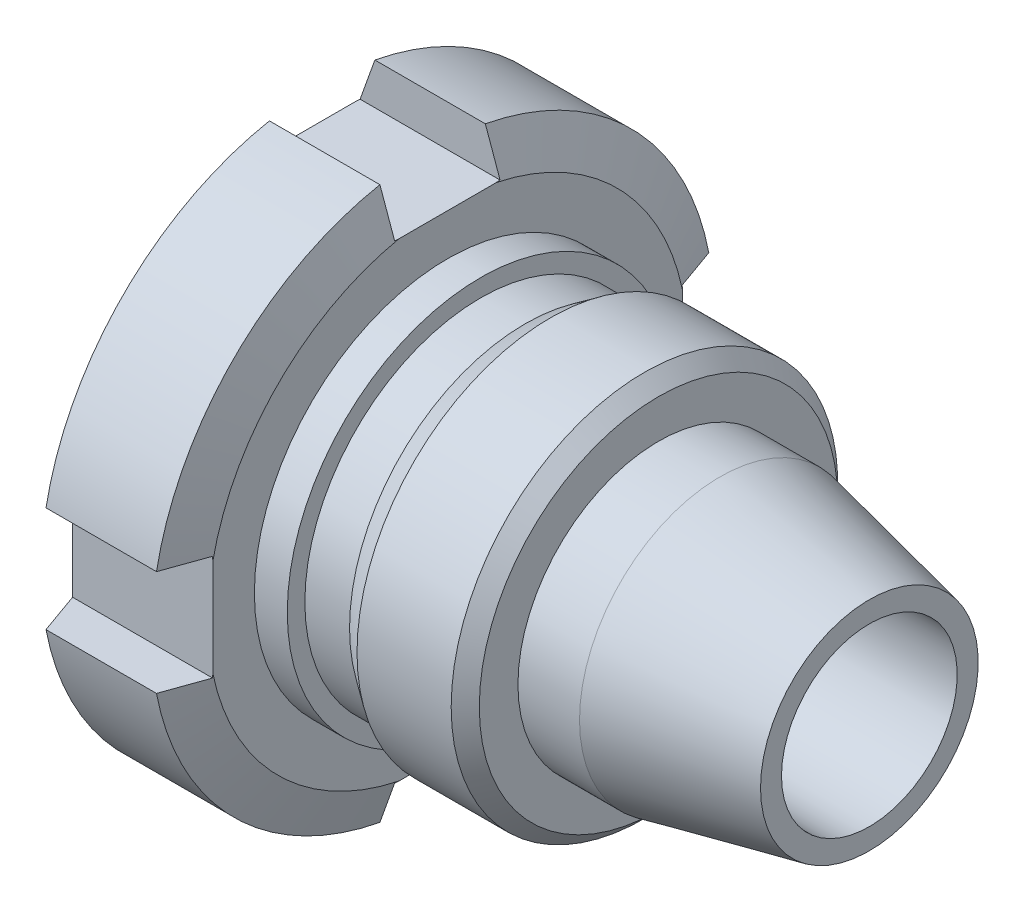
SolidWorks part; units mm, degrees
material "6061-T6 (SS)"
ref_plane "Front Plane" through (0, 0, 0) normal (0, 0, 1) x (1, 0, 0)
ref_plane "Top Plane" through (0, 0, 0) normal (0, 1, 0) x (1, 0, 0)
ref_plane "Right Plane" through (0, 0, 0) normal (1, 0, 0) x (0, 0, -1)
sketch "Sketch1" plane through (0, 0, 0) normal (0, 0, 1) x (1, 0, 0)
  line L0 (0, 6.35) -> (0, 21.6662)
  line L1 (1.359, 25.4) -> (11.341, 25.4)
  line L2 (12.7, 21.6662) -> (12.7, 17.4625)
  line L3 (12.7, 17.4625) -> (15.6718, 17.4625)
  line L4 (15.6718, 17.4625) -> (15.6718, 15.875)
  line L5 (15.6718, 15.875) -> (19.7104, 15.875)
  line L6 (19.7104, 15.875) -> (21.971, 17.4625)
  line L7 (21.971, 17.4625) -> (30.48, 17.4625)
  line L8 (31.75, 16.1925) -> (31.75, 12.7)
  line L9 (31.75, 12.7) -> (37.3126, 12.7)
  line L10 (37.3126, 12.7) -> (50.8, 9.8332)
  line L11 (50.8, 9.8332) -> (50.8, 7.9375)
  line L12 (50.8, 7.9375) -> (38.1, 7.9375)
  line L14 (37.1461, 6.35) -> (0, 6.35)
  line L15 (0, 0) -> (50.8, 0) construction
  line L16 (0, 21.6662) -> (1.359, 25.4)
  line L17 (12.7, 21.6662) -> (11.341, 25.4)
  line L18 (38.1, 7.9375) -> (37.1461, 6.35)
  line L19 (30.48, 17.4625) -> (31.75, 16.1925)
  point P10 (31.75, 17.4625)
  dimension "D1" = 50.8
  dimension "D3" = 12
  dimension "D4" = 25.4
  dimension "D5" = 6.35
  dimension "D6" = 7.9375
  dimension "D7" = 13.4874
  dimension "D8" = 19.05
  dimension "D9" = 28.829
  dimension "D10" = 31.0896
  dimension "D11" = 35.1282
  dimension "D12" = 38.1
  dimension "D13" = 17.4625
  dimension "D14" = 15.875
  dimension "D15" = 12.7
  dimension "D16" = 3.7338
  dimension "D17" = 20
  dimension "D18" = 20
  dimension "D19" = 3.7338
  dimension "D20" = 59
  dimension "D21" = 12.7
revolve "Revolve1" add sketch "Sketch1" angle 360 about L15
sketch "Sketch2" plane through (0, 0, 0) normal (-1, 0, 0) x (0, 0, 1)
  line L0 (0, 0) -> (0, 25.4) construction
  line L1 (-4.7625, 21.2157) -> (-4.7625, 24.9495)
  line L2 (4.7625, 21.2157) -> (4.7625, 24.9495)
  line L3 (-4.7625, 21.2157) -> (4.7625, 21.2157)
  circle A0 centre (0, 0) radius 25.4 construction
  arc A1 (4.7625, 24.9495) -> (-4.7625, 24.9495) centre (0, 0) ccw
  dimension "D1" = 9.525
  dimension "D2" = 4.7625
  dimension "D3" = 3.7338
extrude "Cut-Extrude1" cut sketch "Sketch2" against normal up to next
pattern_circular "CirPattern1" count 4 over 360 about axis through (0, 0, 0) along (1, 0, 0) of "Cut-Extrude1"
